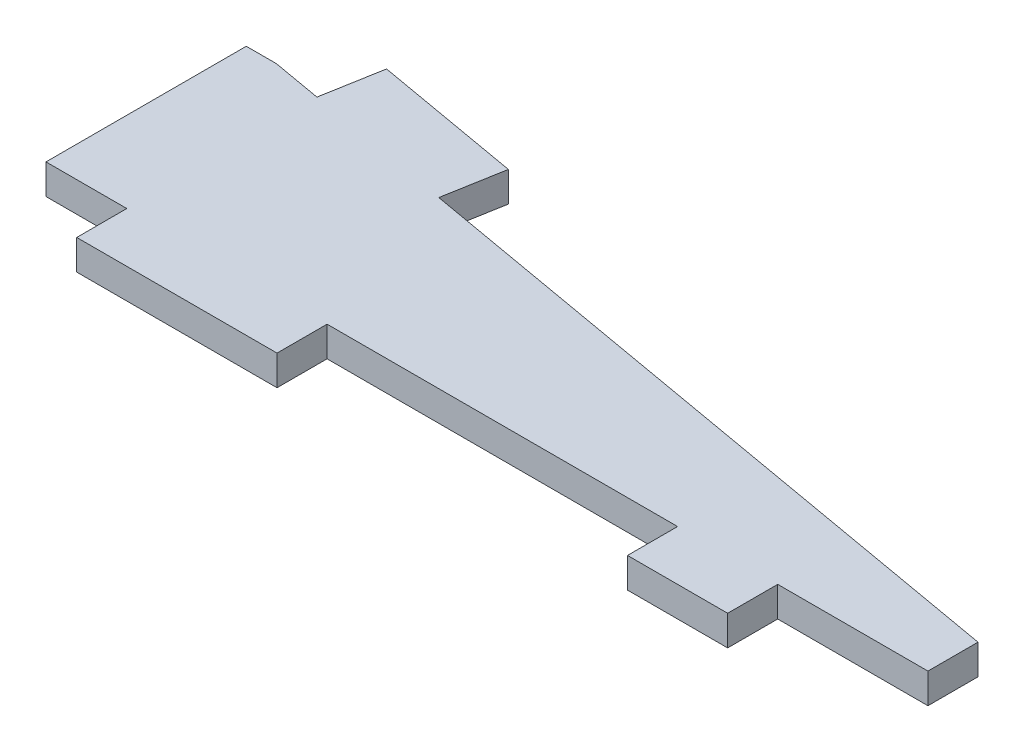
SolidWorks part; units mm, degrees
ref_plane "Front Plane" through (0, 0, 0) normal (0, 0, 1) x (1, 0, 0)
ref_plane "Top Plane" through (0, 0, 0) normal (0, 1, 0) x (1, 0, 0)
ref_plane "Right Plane" through (0, 0, 0) normal (1, 0, 0) x (0, 0, -1)
sketch "Sketch1" plane through (0, 0, 0) normal (0, 1, 0) x (1, 0, 0)
  line L0 (0, 5) -> (-8.0692, 5)
  line L1 (0, 0) -> (20, 0)
  line L2 (0, 0) -> (0, 5)
  line L3 (0, 5) -> (20, 5)
  line L4 (20, 0) -> (20, 5)
  line L9 (-8.0692, 5) -> (-8.0692, 25)
  line L10 (-8.0692, 25) -> (-5.0692, 25)
  line L11 (80, 5) -> (80, 10)
  line L12 (80, 5) -> (20, 5)
  line L13 (80, 10) -> (-5.0692, 25)
  dimension "D1" = 5
  dimension "D2" = 20
  dimension "D3" = 80
  dimension "D4" = 20
  dimension "D5" = 3
  dimension "D6" = 60
  dimension "D7" = 5
extrude "Boss-Extrude1" add sketch "Sketch1" along normal blind 3
sketch "Sketch2" plane through (0, 3, 0) normal (0, 1, 0) x (1, 0, 0)
  line L0 (80, 5) -> (80, 10) construction
  line L1 (65, 5) -> (55, 5)
  line L2 (65, 5) -> (65, 0)
  line L3 (65, 0) -> (55, 0)
  line L4 (55, 5) -> (55, 0)
  line L5 (80, 5) -> (20, 5) construction
  dimension "D1" = 10
  dimension "D2" = 5
  dimension "D3" = 15
extrude "Boss-Extrude2" add sketch "Sketch2" against normal blind 3
sketch "Sketch3" plane through (0, 3, 0) normal (0, 1, 0) x (1, 0, 0)
  line L0 (-0.1452, 24.1318) -> (14.6269, 21.527)
  line L1 (80, 10) -> (-5.0692, 25) construction
  line L2 (14.6269, 21.527) -> (15.6688, 27.4359)
  line L3 (15.6688, 27.4359) -> (0.8967, 30.0406)
  line L4 (0.8967, 30.0406) -> (-0.1452, 24.1318)
  dimension "D1" = 6
  dimension "D2" = 15
  dimension "D3" = 5
extrude "Boss-Extrude3" add sketch "Sketch3" against normal blind 3
